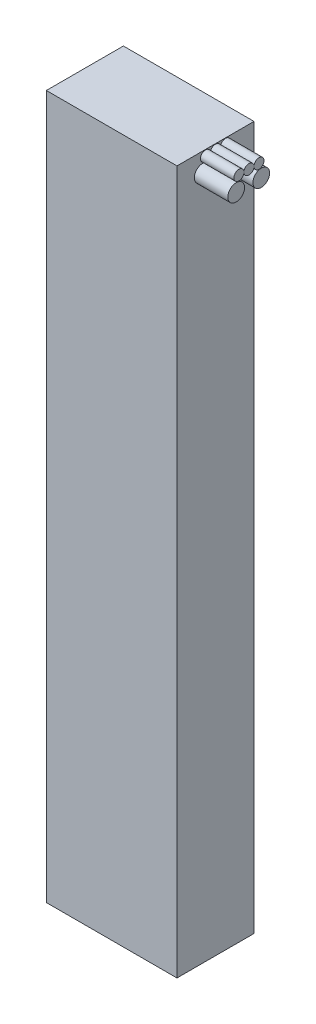
SolidWorks part; units mm, degrees
ref_plane "Front Plane" through (0, 0, 0) normal (0, 0, 1) x (1, 0, 0)
ref_plane "Top Plane" through (0, 0, 0) normal (0, 1, 0) x (1, 0, 0)
ref_plane "Right Plane" through (0, 0, 0) normal (1, 0, 0) x (0, 0, -1)
sketch "Sketch1" plane through (0, 0, 0) normal (0, 1, 0) x (1, 0, 0)
  line L1 (-9.75, -5.75) -> (9.75, -5.75)
  line L2 (-9.75, -5.75) -> (-9.75, 5.75)
  line L3 (-9.75, 5.75) -> (9.75, 5.75)
  line L4 (9.75, -5.75) -> (9.75, 5.75)
  line L5 (-9.75, -5.75) -> (9.75, 5.75) construction
  line L6 (-9.75, 5.75) -> (9.75, -5.75) construction
  point P0 (0, 0)
  dimension "D1" = 19.5
  dimension "D2" = 11.5
extrude "Boss-Extrude1" add sketch "Sketch1" along normal blind 105
sketch "Sketch2" plane through (9.75, 0, 0) normal (1, 0, 0) x (0, 0, -1)
  line L0 (0, 105) -> (0, 100.7656) construction
  line L1 (-5.75, 105) -> (5.75, 105) construction
  circle A0 centre (-1.5, 104.1895) radius 0.75
  circle A1 centre (0, 104.1895) radius 0.75
  circle A2 centre (1.5, 104.1895) radius 0.75
  circle A3 centre (-1.9087, 102.1582) radius 1.25
  circle A4 centre (1.8361, 102.1582) radius 1.25
  dimension "D1" = 1.5
  dimension "D2" = 1.5
  dimension "D3" = 1.5
  dimension "D4" = 2.5
  dimension "D5" = 2.5
extrude "Boss-Extrude3" add sketch "Sketch2" along normal blind 5 separate body contours A0 | A3 | L0 A1 | A1 L0 | A2 | A4
